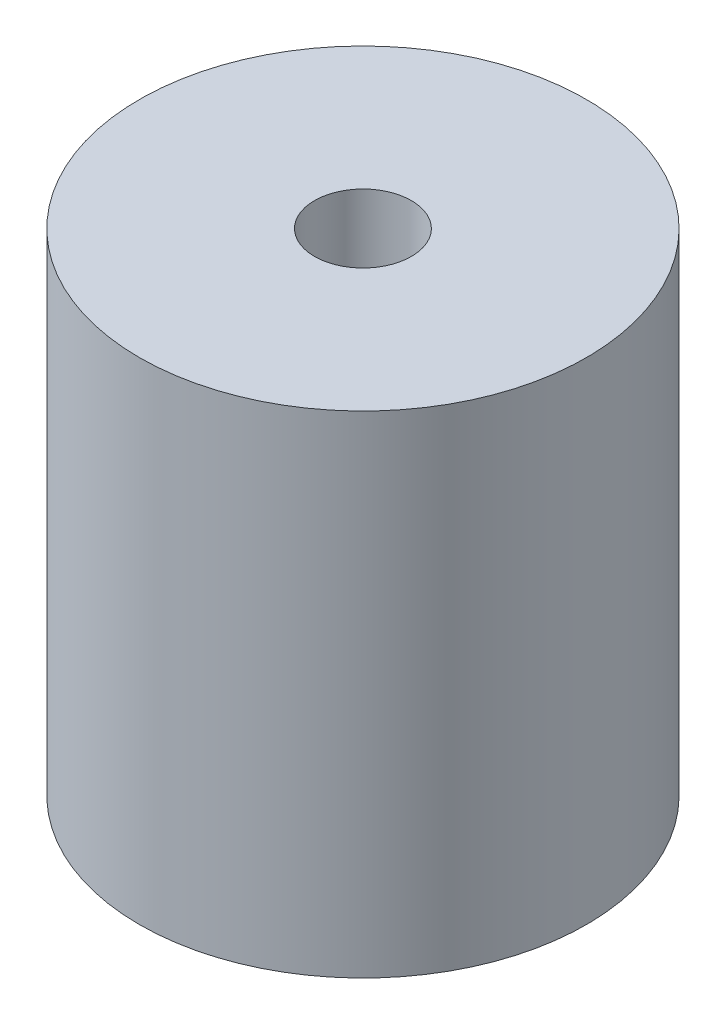
SolidWorks part; units mm, degrees
ref_plane "Front Plane" through (0, 0, 0) normal (0, 0, 1) x (1, 0, 0)
ref_plane "Top Plane" through (0, 0, 0) normal (0, 1, 0) x (1, 0, 0)
ref_plane "Right Plane" through (0, 0, 0) normal (1, 0, 0) x (0, 0, -1)
sketch "Esboço1" plane through (0, 0, 0) normal (0, 1, 0) x (1, 0, 0)
  circle A0 centre (0, 0) radius 6.5
  circle A1 centre (0, 0) radius 30
  dimension "D1" = 13
  dimension "D2" = 60
extrude "Ressalto-extrusão1" add sketch "Esboço1" along normal blind 65.9
